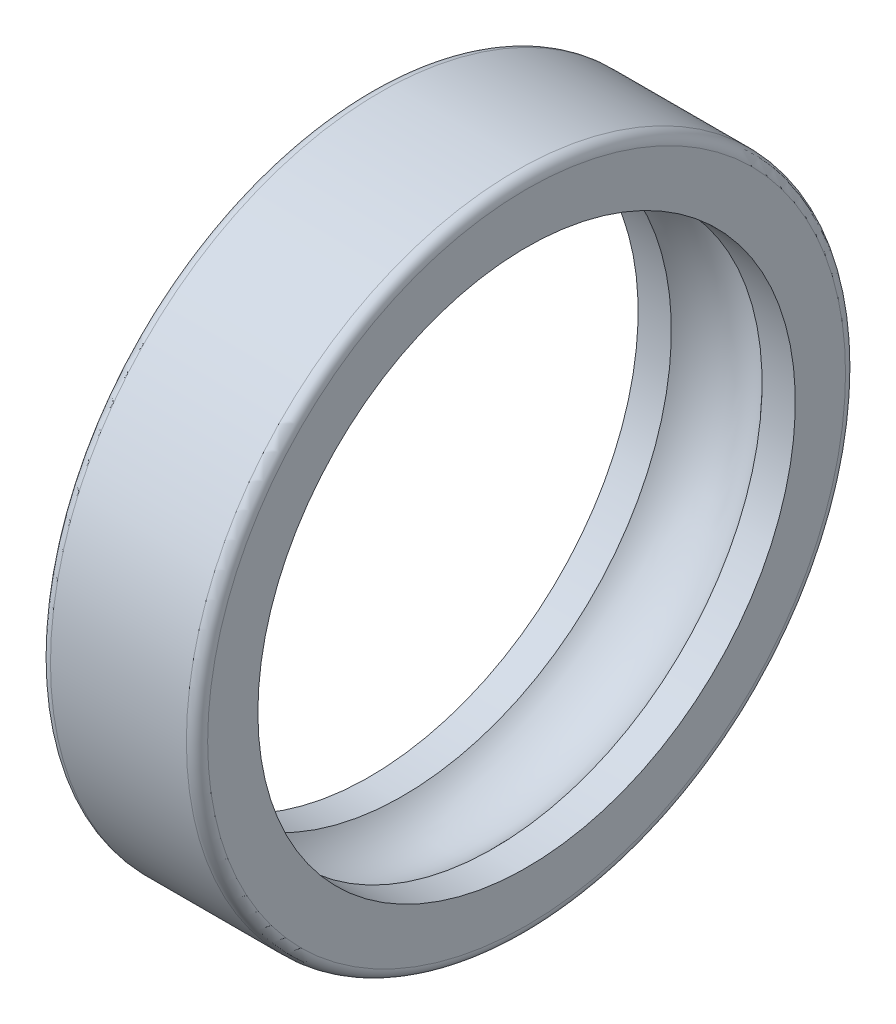
SolidWorks part; units mm, degrees
ref_plane "Front Plane" through (0, 0, 0) normal (0, 0, 1) x (1, 0, 0)
ref_plane "Top Plane" through (0, 0, 0) normal (0, 1, 0) x (1, 0, 0)
ref_plane "Right Plane" through (0, 0, 0) normal (1, 0, 0) x (0, 0, -1)
sketch "Sketch1" plane through (0, 0, 0) normal (0, 1, 0) x (1, 0, 0)
  line L0 (0, 59) -> (0, 0) construction
  line L1 (15.5, 65) -> (-15.5, 65)
  line L2 (15.5, 65) -> (15.5, 53)
  line L3 (15.5, 53) -> (8.9443, 53)
  line L4 (-15.5, 65) -> (-15.5, 53)
  line L5 (15.5, 65) -> (-15.5, 53) construction
  line L6 (15.5, 53) -> (-15.5, 65) construction
  line L7 (-67.7311, 0) -> (67.7311, 0) construction
  line L8 (-15.5, 53) -> (-8.9443, 53)
  arc A0 (-8.9443, 53) -> (8.9443, 53) centre (0, 45) cw
  point P0 (0, 59)
  point P13 (0, 0)
  point P14 (0, 0)
  dimension "D5" = 12
  dimension "D1" = 31
  dimension "D2" = 53
  dimension "D3" = 65
  dimension "D4" = 8
revolve "Revolve1" add sketch "Sketch1" angle 360 about L7
fillet "Fillet1" radius 2.1 2 edges at (15.5, 0, 65) (-15.5, 0, 65)
